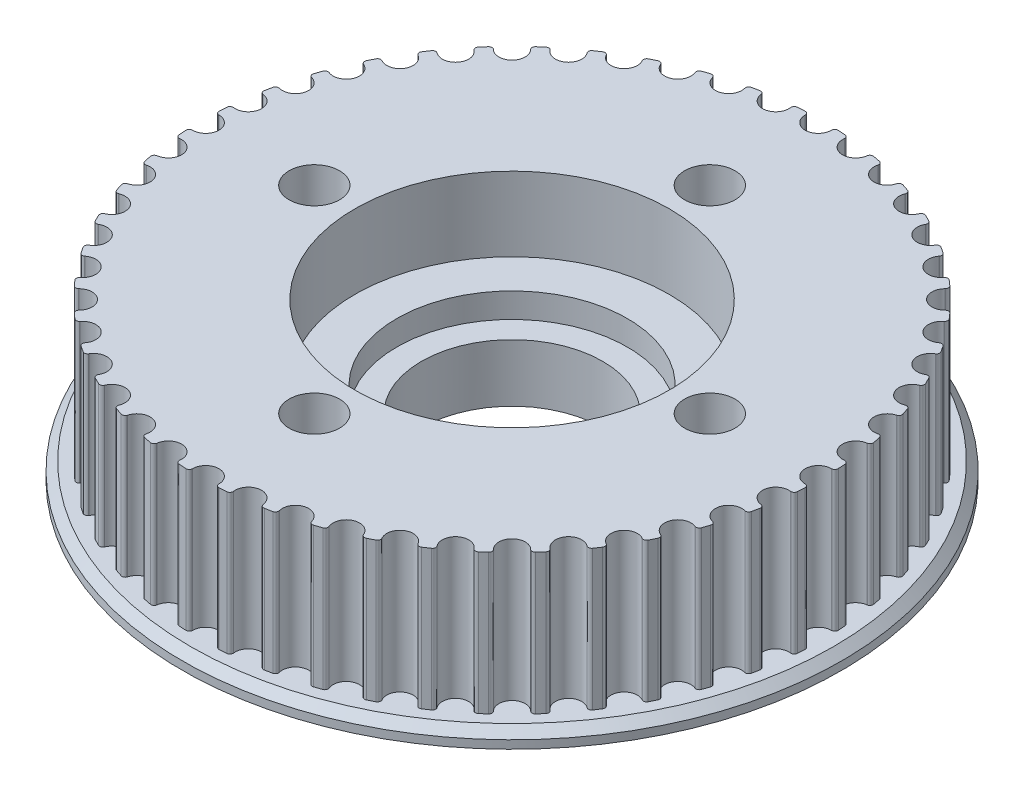
SolidWorks part; units mm, degrees
other "Markup1"
sketch "Sketch11" plane through (-40, 17, -40) normal (-0.9203, 0.0597, -0.3866) x (-0.0954, -0.9927, 0.0739)
material "ABS"
ref_plane "Front Plane" through (0, 0, 0) normal (0, 0, 1) x (1, 0, 0)
ref_plane "Top Plane" through (0, 0, 0) normal (0, 1, 0) x (1, 0, 0)
ref_plane "Right Plane" through (0, 0, 0) normal (1, 0, 0) x (0, 0, -1)
sketch "Sketch4" plane through (0, 0, 0) normal (0, 1, 0) x (1, 0, 0)
  circle A0 centre (0, 0) radius 37.625
  circle A1 centre (0, 0) radius 38.195 construction
  dimension "D1" = 75.25
  dimension "D2" = 76.39
extrude "Boss-Extrude2" add sketch "Sketch4" along normal blind 17
sketch "Sketch5" plane through (0, 17, 0) normal (0, 1, 0) x (1, 0, 0)
  line L0 (0, 0) -> (0, 37.625) construction
  line L1 (-1.6026, 37.2169) -> (-1.6, 37.175)
  line L2 (1.6026, 37.2169) -> (1.6, 37.175)
  line L6 (0, 0) -> (2.4608, 37.5444) construction
  line L7 (0, 0) -> (-2.4608, 37.5444) construction
  circle A2 centre (0, 0) radius 37.625 construction
  arc A3 (2.0215, 37.5707) -> (1.6026, 37.2169) centre (2, 37.1712) ccw
  arc A4 (-1.6026, 37.2169) -> (-2.0215, 37.5707) centre (-2, 37.1712) ccw
  arc A11 (-1.6, 37.175) -> (1.6, 37.175) centre (0, 37.175) ccw
  arc A12 (-2.0215, 37.5707) -> (-2.4608, 37.5444) centre (0, 0) ccw
  arc A13 (2.4608, 37.5444) -> (2.0215, 37.5707) centre (0, 0) ccw
  arc A14 (2.4608, 37.5444) -> (-2.4608, 37.5444) centre (0, 0) ccw
  point P7 (0, 37.625)
  point P18 (0, 35.575)
  dimension "D1" = 0.4
  dimension "D2" = 3.2
  dimension "D6" = 3.75
  dimension "D3" = 2.05
  dimension "D7" = 3.75
extrude "Cut-Extrude5" cut sketch "Sketch5" against normal through all
pattern_circular "CirPattern1" count 48 over 360 about axis through (0, 0, 0) along (0, 1, 0) of "Cut-Extrude5"
sketch "Sketch8" plane through (0, 17, 0) normal (0, 1, 0) x (1, 0, 0)
  circle A0 centre (0, 0) radius 19.075
  dimension "D1" = 38.15
extrude "Cut-Extrude7" cut sketch "Sketch8" against normal blind 12 and the other way through all
sketch "Sketch9" plane through (0, 0, 0) normal (0, -1, 0) x (1, 0, 0)
  circle A0 centre (0, 0) radius 11
  circle A1 centre (0, 24) radius 3.0625
  circle A2 centre (24, 0) radius 3.0625
  circle A3 centre (0, -24) radius 3.0625
  circle A4 centre (-24, 0) radius 3.0625
  point P14 (0, 0)
  dimension "D1" = 22
  dimension "D2" = 6.125
  dimension "D3" = 24
  dimension "D4" = 4
extrude "Cut-Extrude8" cut sketch "Sketch9" against normal through all
sketch "Sketch10" plane through (0, 0, 0) normal (0, -1, 0) x (1, 0, 0)
  circle A0 centre (0, 0) radius 40
  circle A1 centre (0, 24) radius 3.0625
  circle A2 centre (24, 0) radius 3.0625
  circle A3 centre (-24, 0) radius 3.0625
  circle A4 centre (0, -24) radius 3.0625
  circle A5 centre (0, 0) radius 11
  circle A6 centre (0, 0) radius 11 construction
  circle A7 centre (-24, 0) radius 3.0625 construction
  dimension "D1" = 80
extrude "Boss-Extrude3" add sketch "Sketch10" along normal blind 2
chamfer "Chamfer1" distance 1 angle 45 1 edges at (0, 0, -40)
sketch "Sketch12" plane through (0, 5, 0) normal (0, 1, 0) x (1, 0, 0)
  circle A0 centre (0, 0) radius 19.075
  circle A1 centre (0, 0) radius 14
  circle A2 centre (0, 0) radius 19.075 construction
  dimension "D1" = 28
extrude "Boss-Extrude4" add sketch "Sketch12" along normal blind 3
equation "\"n\"= 48'FROM MATLAB ANALYSIS"
equation "\"p\"= 5mm'FROM MATLAB ANALYSIS"
equation "\"pd\"= ( \"n\" * \"p\" ) / pi"
equation "\"w\"= 20.5'PAGE 24 CONTI SYNCHROBELT GUIDLINES"
equation "\"od\"= 75.25mm'ISO13050:2014"
equation "\"Hg\"= 2.06mm'ISO13050:2014"
equation "\"X\"= 0mm'ISO13050:2014"
equation "\"R1\"= 1.6mm'ISO13050:2014"
equation "\"phi\"= 2deg'ISO13050:2014"
equation "\"R2\"= 0.4mm"
